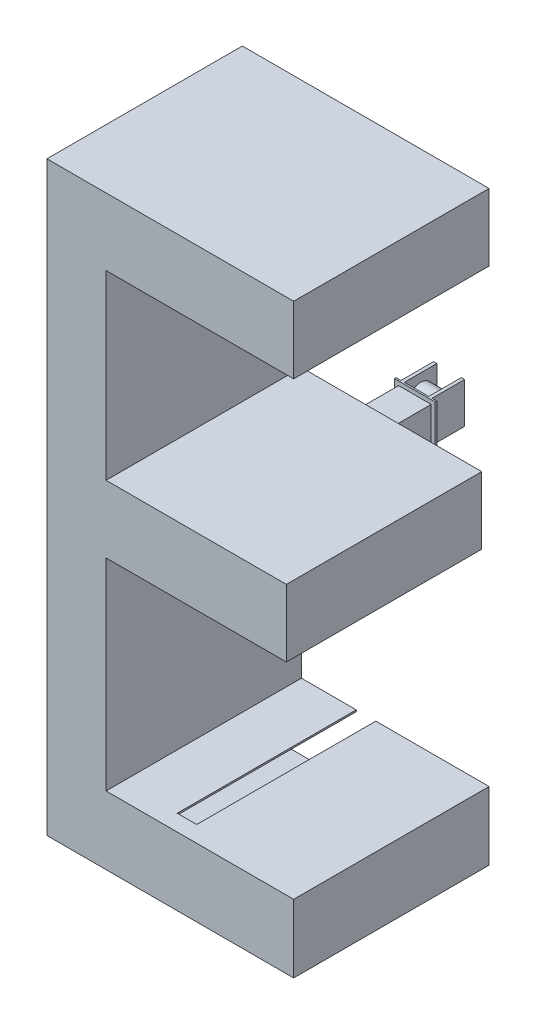
SolidWorks part; units mm, degrees
ref_plane "Front Plane" through (0, 0, 0) normal (0, 0, 1) x (1, 0, 0)
ref_plane "Top Plane" through (0, 0, 0) normal (0, 1, 0) x (1, 0, 0)
ref_plane "Right Plane" through (0, 0, 0) normal (1, 0, 0) x (0, 0, -1)
sketch "Sketch2" plane through (0, 0, 0) normal (0, 0, 1) x (1, 0, 0)
  text T0 "E" font "Consolas" height 914.4
extrude "Boss-Extrude4" add sketch "Sketch2" against normal blind 304.8
shell "Shell1" thickness 2.54
sketch "Sketch3" plane through (0, 0, -2.54) normal (0, 0, -1) x (-1, 0, 0)
  line L2 (-320.1719, 447.9288) -> (-269.3719, 447.9288)
  line L3 (-320.1719, 447.9288) -> (-320.1719, 498.7288)
  line L4 (-320.1719, 498.7288) -> (-269.3719, 498.7288)
  line L5 (-269.3719, 447.9288) -> (-269.3719, 498.7288)
  line L6 (-104.2719, 0) -> (-104.2719, 914.4) construction
  dimension "D1" = 165.1
  dimension "D3" = 50.8
  dimension "D4" = 50.8
extrude "Boss-Extrude5" add sketch "Sketch3" along normal blind 381
sketch "Sketch4" plane through (0, 0, -383.54) normal (0, 0, -1) x (-1, 0, 0)
  line L0 (-269.3719, 498.7288) -> (-320.1719, 498.7288) construction
  line L1 (-326.5219, 441.5788) -> (-263.0219, 441.5788)
  line L2 (-326.5219, 441.5788) -> (-326.5219, 505.0788)
  line L3 (-326.5219, 505.0788) -> (-263.0219, 505.0788)
  line L4 (-263.0219, 441.5788) -> (-263.0219, 505.0788)
  line L5 (-326.5219, 441.5788) -> (-263.0219, 505.0788) construction
  line L6 (-326.5219, 505.0788) -> (-263.0219, 441.5788) construction
  line L7 (-320.1719, 498.7288) -> (-320.1719, 447.9288) construction
  point P0 (-294.7719, 473.3288)
  dimension "D1" = 63.5
  dimension "D2" = 63.5
  dimension "D3" = 6.35
  dimension "D4" = 6.35
extrude "Boss-Extrude6" add sketch "Sketch4" along normal blind 2.54
sketch "Sketch5" plane through (0, 0, -386.08) normal (0, 0, -1) x (-1, 0, 0)
  line L0 (-263.0219, 505.0788) -> (-326.5219, 505.0788) construction
  line L1 (-318.9019, 441.5788) -> (-313.8219, 441.5788)
  line L2 (-318.9019, 441.5788) -> (-318.9019, 505.0788)
  line L3 (-318.9019, 505.0788) -> (-313.8219, 505.0788)
  line L4 (-313.8219, 441.5788) -> (-313.8219, 505.0788)
  line L5 (-263.0219, 441.5788) -> (-263.0219, 505.0788) construction
  line L6 (-270.6419, 441.8662) -> (-275.7219, 441.8662)
  line L7 (-270.6419, 441.8662) -> (-270.6419, 505.0788)
  line L8 (-270.6419, 505.0788) -> (-275.7219, 505.0788)
  line L9 (-275.7219, 441.8662) -> (-275.7219, 505.0788)
  line L10 (-326.5219, 505.0788) -> (-326.5219, 441.5788) construction
  dimension "D1" = 5.08
  dimension "D2" = 5.08
  dimension "D3" = 7.62
  dimension "D4" = 7.62
extrude "Boss-Extrude7" add sketch "Sketch5" along normal blind 50.8
sketch "Sketch6" plane through (313.8219, 0, 0) normal (-1, 0, 0) x (0, 0, 1)
  line L0 (-386.08, 441.5788) -> (-383.54, 441.5788) construction
  line L1 (-436.88, 441.8662) -> (-436.88, 505.0788) construction
  circle A0 centre (-411.48, 473.3288) radius 19.05
  dimension "D1" = 38.1
  dimension "D2" = 31.75
  dimension "D3" = 25.4
extrude "Boss-Extrude8" add sketch "Sketch6" along normal up to next
sketch "Sketch7" plane through (0, 0, 0) normal (0, -1, 0) x (1, 0, 0)
  line L0 (104.2719, -304.8) -> (104.2719, 0) construction
  line L3 (282.0719, -304.8) -> (312.5519, -304.8)
  line L6 (489.2278, -304.8) -> (104.2719, -304.8) construction
  line L7 (282.0719, -304.8) -> (282.0719, -25.4)
  line L8 (282.0719, -25.4) -> (312.5519, -25.4)
  line L9 (312.5519, -25.4) -> (312.5519, -304.8)
  dimension "D1" = 30.48
  dimension "D2" = 279.4
  dimension "D3" = 0
  dimension "D4" = 177.8
extrude "Cut-Extrude1" cut sketch "Sketch7" against normal blind 431.8
